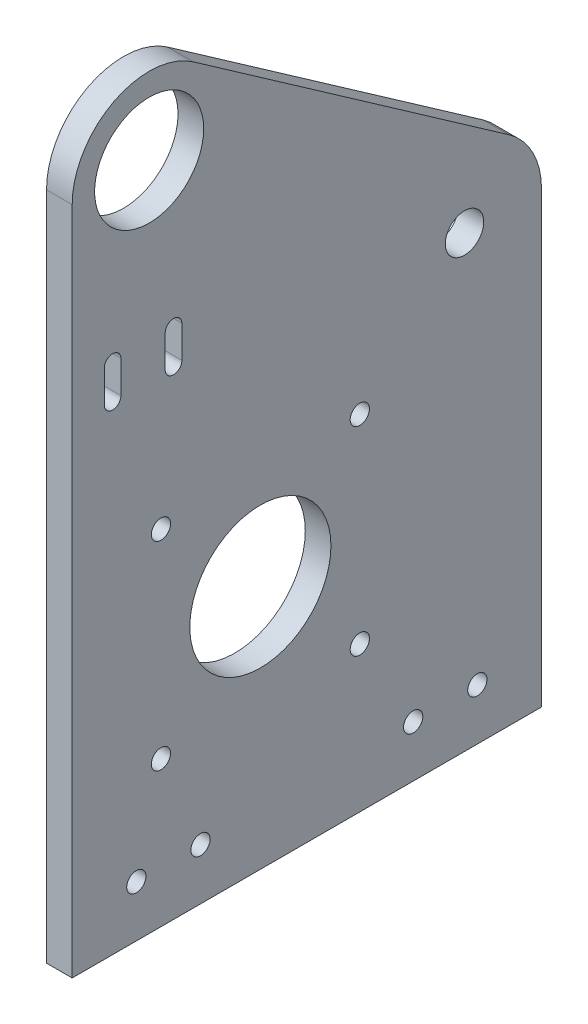
SolidWorks part; units mm, degrees
ref_plane "前视基准面" through (0, 0, 0) normal (0, 0, 1) x (1, 0, 0)
ref_plane "上视基准面" through (0, 0, 0) normal (0, 1, 0) x (1, 0, 0)
ref_plane "右视基准面" through (0, 0, 0) normal (1, 0, 0) x (0, 0, -1)
sketch "草图1" plane through (0, 0, 0) normal (1, 0, 0) x (0, 0, -1)
  line L0 (0, 0) -> (-49.1551, 34.406) construction
  line L1 (0, 0) -> (-49.1551, 0) construction
  line L2 (-49.1551, 34.406) -> (-49.1551, 0) construction
  line L3 (-42.2739, 44.237) -> (6.8812, 9.831)
  line L4 (12, 0) -> (12, -70)
  line L5 (-61.1551, 34.406) -> (-61.1551, -70)
  line L6 (-61.1551, -70) -> (12, -70)
  line L7 (0, 0) -> (-31.8198, -31.8198) construction
  line L8 (12, -70) -> (12, -62)
  line L9 (12, -62) -> (2, -62) construction
  line L10 (2, -62) -> (-8, -62) construction
  line L11 (-61.1551, -70) -> (-61.1551, -62)
  line L12 (-61.1551, -62) -> (-51.1551, -62) construction
  line L13 (-51.1551, -62) -> (-41.1551, -62) construction
  line L14 (-31.8198, -31.8198) -> (-16.3198, -31.8198) construction
  line L15 (-16.3198, -31.8198) -> (-16.3198, -16.3198) construction
  line L16 (-61.1551, 9.831) -> (-56.1551, 9.831) construction
  line L17 (-53.5551, 9.831) -> (-53.5551, 4.831)
  line L18 (-53.5551, 4.831) -> (-56.1551, 4.831) construction
  line L19 (-56.1551, 4.831) -> (-56.1551, 9.831)
  line L20 (-44.0551, 9.831) -> (-44.0551, 4.831)
  line L21 (-46.6551, 4.831) -> (-46.6551, 9.831)
  circle A0 centre (0, 0) radius 3
  arc A1 (-61.1551, 34.406) -> (-42.2739, 44.237) centre (-49.1551, 34.406) cw
  circle A2 centre (-49.1551, 34.406) radius 8.5
  arc A3 (6.8812, 9.831) -> (12, 0) centre (0, 0) cw
  circle A4 centre (-31.8198, -31.8198) radius 11
  circle A5 centre (2, -62) radius 1.5
  circle A6 centre (-8, -62) radius 1.5
  circle A7 centre (-41.1551, -62) radius 1.5
  circle A8 centre (-51.1551, -62) radius 1.5
  circle A9 centre (-16.3198, -16.3198) radius 1.5
  circle A10 centre (-16.3198, -47.3198) radius 1.5
  circle A11 centre (-47.3198, -47.3198) radius 1.5
  circle A12 centre (-47.3198, -16.3198) radius 1.5
  arc A13 (-56.1551, 9.831) -> (-53.5551, 9.831) centre (-54.8551, 9.831) cw
  arc A14 (-53.5551, 4.831) -> (-56.1551, 4.831) centre (-54.8551, 4.831) cw
  arc A15 (-46.6551, 9.831) -> (-44.0551, 9.831) centre (-45.3551, 9.831) cw
  arc A16 (-44.0551, 4.831) -> (-46.6551, 4.831) centre (-45.3551, 4.831) cw
  point P35 (-31.8198, -31.8198)
  dimension "D3" = 17
  dimension "D4" = 8
  dimension "D5" = 70
  dimension "D7" = 10
  dimension "D9" = 10
  dimension "D11" = 6
  dimension "D12" = 22
  dimension "D15" = 4
  dimension "D16" = 5
  dimension "D17" = 5
  dimension "D1" = 60
  dimension "D2" = 34.406
  dimension "D6" = 45
  dimension "D8" = 10
  dimension "D10" = 10
  dimension "D13" = 15.5
  dimension "D14" = 15.5
  dimension "D18" = 2
extrude "凸台-拉伸1" add sketch "草图1" along normal blind 4 contours A3 L3 A1 L5 L6 L4 A4 A2 A0
